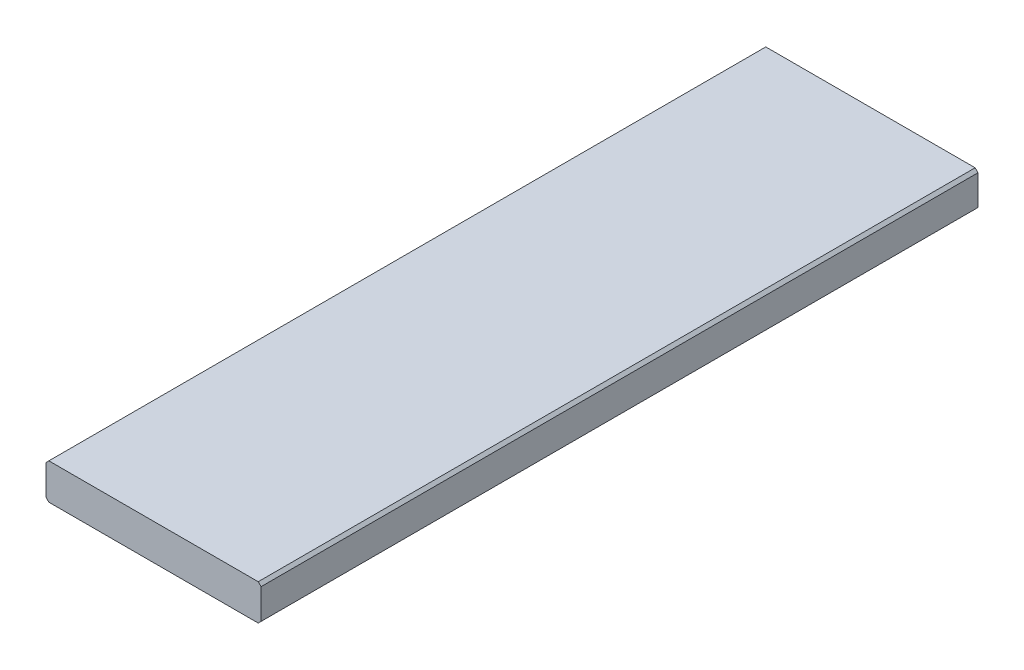
SolidWorks part; units mm, degrees
ref_plane "Спереди" through (0, 0, 0) normal (0, 0, 1) x (1, 0, 0)
ref_plane "Сверху" through (0, 0, 0) normal (0, 1, 0) x (1, 0, 0)
ref_plane "Справа" through (0, 0, 0) normal (1, 0, 0) x (0, 0, -1)
sketch "Эскиз1" plane through (0, 0, 0) normal (0, 0, 1) x (1, 0, 0)
  line L0 (-75, 10.5) -> (-73, 12.5)
  line L1 (-73, 12.5) -> (73, 12.5)
  line L2 (-75, 10.5) -> (-75, -10.5)
  line L3 (-73, -12.5) -> (73, -12.5)
  line L4 (75, 10.5) -> (75, -10.5)
  line L5 (-75, 12.5) -> (75, -12.5) construction
  line L6 (-75, -12.5) -> (75, 12.5) construction
  line L7 (-75, -10.5) -> (-73, -12.5)
  line L8 (73, -12.5) -> (75, -10.5)
  line L9 (73, 12.5) -> (75, 10.5)
  point P0 (0, 0)
  dimension "D1" = 150
  dimension "D2" = 25
extrude "Бобышка-Вытянуть1" add sketch "Эскиз1" along normal blind 500
